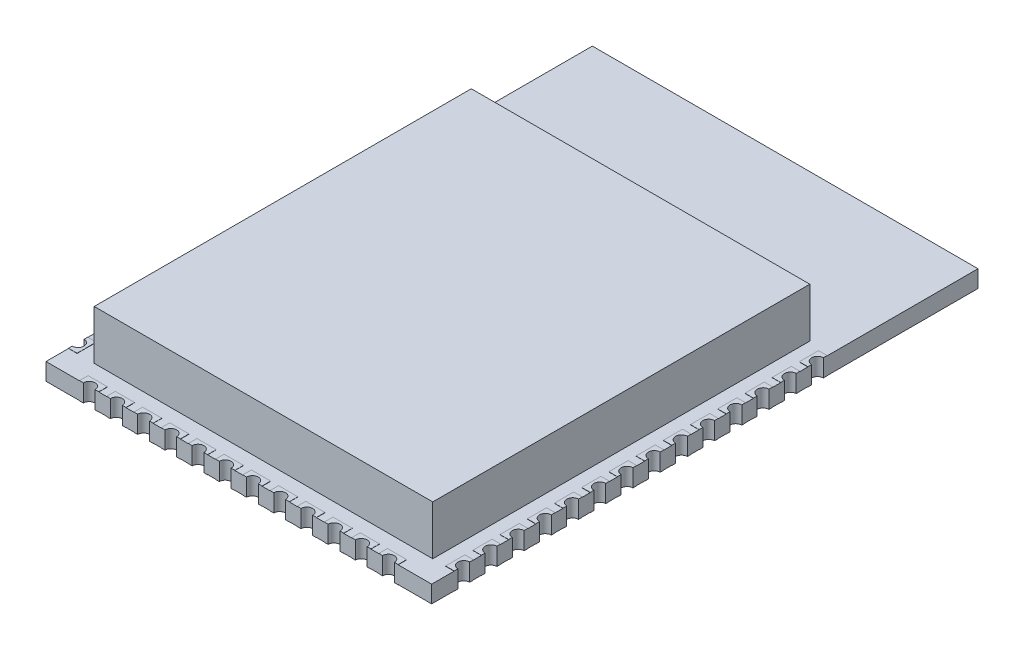
SolidWorks part; units mm, degrees
ref_plane "Front Plane" through (0, 0, 0) normal (0, 0, 1) x (1, 0, 0)
ref_plane "Top Plane" through (0, 0, 0) normal (0, 1, 0) x (1, 0, 0)
ref_plane "Right Plane" through (0, 0, 0) normal (1, 0, 0) x (0, 0, -1)
sketch "Sketch1" plane through (0, 0, 0) normal (0, 1, 0) x (1, 0, 0)
  line L5 (-9, 0) -> (9, 0)
  line L6 (-9, 0) -> (-9, -25.5)
  line L7 (-9, -25.5) -> (9, -25.5)
  line L8 (9, 0) -> (9, -25.5)
  dimension "D1" = 18
  dimension "D2" = 25.5
extrude "Boss-Extrude1" add sketch "Sketch1" along normal blind 0.8
sketch "Sketch2" plane through (0, 0.8, 0) normal (0, 1, 0) x (1, 0, 0)
  line L0 (-9, 0) -> (-9, -25.5) construction
  line L1 (-9, -23.55) -> (-8.6, -23.55)
  line L2 (-9, -23.55) -> (-9, -24.45)
  line L3 (-9, -24.45) -> (-8.6, -24.45)
  line L4 (-8.6, -23.55) -> (-8.6, -24.45)
  line L5 (-8.6, -24) -> (-6.8619, -24) construction
  line L6 (-9, -25.5) -> (9, -25.5) construction
  line L7 (-9, -23.18) -> (-8.6, -23.18)
  line L8 (-8.6, -22.28) -> (-8.6, -23.18)
  line L9 (-9, -22.28) -> (-8.6, -22.28)
  line L10 (-9, -22.28) -> (-9, -23.18)
  line L11 (-9, -21.91) -> (-8.6, -21.91)
  line L12 (-8.6, -21.01) -> (-8.6, -21.91)
  line L13 (-9, -21.01) -> (-8.6, -21.01)
  line L14 (-9, -21.01) -> (-9, -21.91)
  line L15 (-9, -20.64) -> (-8.6, -20.64)
  line L16 (-8.6, -19.74) -> (-8.6, -20.64)
  line L17 (-9, -19.74) -> (-8.6, -19.74)
  line L18 (-9, -19.74) -> (-9, -20.64)
  line L19 (-9, -19.37) -> (-8.6, -19.37)
  line L20 (-8.6, -18.47) -> (-8.6, -19.37)
  line L21 (-9, -18.47) -> (-8.6, -18.47)
  line L22 (-9, -18.47) -> (-9, -19.37)
  line L23 (-9, -18.1) -> (-8.6, -18.1)
  line L24 (-8.6, -17.2) -> (-8.6, -18.1)
  line L25 (-9, -17.2) -> (-8.6, -17.2)
  line L26 (-9, -17.2) -> (-9, -18.1)
  line L27 (-9, -16.83) -> (-8.6, -16.83)
  line L28 (-8.6, -15.93) -> (-8.6, -16.83)
  line L29 (-9, -15.93) -> (-8.6, -15.93)
  line L30 (-9, -15.93) -> (-9, -16.83)
  line L31 (-9, -15.56) -> (-8.6, -15.56)
  line L32 (-8.6, -14.66) -> (-8.6, -15.56)
  line L33 (-9, -14.66) -> (-8.6, -14.66)
  line L34 (-9, -14.66) -> (-9, -15.56)
  line L35 (-9, -14.29) -> (-8.6, -14.29)
  line L36 (-8.6, -13.39) -> (-8.6, -14.29)
  line L37 (-9, -13.39) -> (-8.6, -13.39)
  line L38 (-9, -13.39) -> (-9, -14.29)
  line L39 (-9, -13.02) -> (-8.6, -13.02)
  line L40 (-8.6, -12.12) -> (-8.6, -13.02)
  line L41 (-9, -12.12) -> (-8.6, -12.12)
  line L42 (-9, -12.12) -> (-9, -13.02)
  line L43 (-9, -11.75) -> (-8.6, -11.75)
  line L44 (-8.6, -10.85) -> (-8.6, -11.75)
  line L45 (-9, -10.85) -> (-8.6, -10.85)
  line L46 (-9, -10.85) -> (-9, -11.75)
  line L47 (-9, -10.48) -> (-8.6, -10.48)
  line L48 (-8.6, -9.58) -> (-8.6, -10.48)
  line L49 (-9, -9.58) -> (-8.6, -9.58)
  line L50 (-9, -9.58) -> (-9, -10.48)
  line L51 (-9, -9.21) -> (-8.6, -9.21)
  line L52 (-8.6, -8.31) -> (-8.6, -9.21)
  line L53 (-9, -8.31) -> (-8.6, -8.31)
  line L54 (-9, -8.31) -> (-9, -9.21)
  line L55 (-9, -7.94) -> (-8.6, -7.94)
  line L56 (-8.6, -7.04) -> (-8.6, -7.94)
  line L57 (-9, -7.04) -> (-8.6, -7.04)
  line L58 (-9, -7.04) -> (-9, -7.94)
  line L63 (-9, -6.67) -> (-8.6, -6.67) [skipped]
  line L64 (-8.6, -5.77) -> (-8.6, -6.67) [skipped]
  line L65 (-9, -5.77) -> (-8.6, -5.77) [skipped]
  line L66 (-9, -5.77) -> (-9, -6.67) [skipped]
  line L67 (0, -25.5) -> (0, -12.4849) construction
  line L68 (9, -7.04) -> (9, -7.94)
  line L69 (9, -7.04) -> (8.6, -7.04)
  line L70 (8.6, -7.04) -> (8.6, -7.94)
  line L71 (9, -7.94) -> (8.6, -7.94)
  line L72 (9, -8.31) -> (9, -9.21)
  line L73 (9, -8.31) -> (8.6, -8.31)
  line L74 (8.6, -8.31) -> (8.6, -9.21)
  line L75 (9, -9.21) -> (8.6, -9.21)
  line L76 (9, -9.58) -> (9, -10.48)
  line L77 (9, -9.58) -> (8.6, -9.58)
  line L78 (8.6, -9.58) -> (8.6, -10.48)
  line L79 (9, -10.48) -> (8.6, -10.48)
  line L80 (9, -10.85) -> (9, -11.75)
  line L81 (9, -10.85) -> (8.6, -10.85)
  line L82 (8.6, -10.85) -> (8.6, -11.75)
  line L83 (9, -11.75) -> (8.6, -11.75)
  line L84 (9, -12.12) -> (9, -13.02)
  line L85 (9, -12.12) -> (8.6, -12.12)
  line L86 (8.6, -12.12) -> (8.6, -13.02)
  line L87 (9, -13.02) -> (8.6, -13.02)
  line L88 (9, -13.39) -> (9, -14.29)
  line L89 (9, -13.39) -> (8.6, -13.39)
  line L90 (8.6, -13.39) -> (8.6, -14.29)
  line L91 (9, -14.29) -> (8.6, -14.29)
  line L92 (9, -14.66) -> (9, -15.56)
  line L93 (9, -14.66) -> (8.6, -14.66)
  line L94 (8.6, -14.66) -> (8.6, -15.56)
  line L95 (9, -15.56) -> (8.6, -15.56)
  line L96 (9, -15.93) -> (9, -16.83)
  line L97 (9, -15.93) -> (8.6, -15.93)
  line L98 (8.6, -15.93) -> (8.6, -16.83)
  line L99 (9, -16.83) -> (8.6, -16.83)
  line L100 (9, -17.2) -> (9, -18.1)
  line L101 (9, -17.2) -> (8.6, -17.2)
  line L102 (8.6, -17.2) -> (8.6, -18.1)
  line L103 (9, -18.1) -> (8.6, -18.1)
  line L104 (9, -18.47) -> (9, -19.37)
  line L105 (9, -18.47) -> (8.6, -18.47)
  line L106 (8.6, -18.47) -> (8.6, -19.37)
  line L107 (9, -19.37) -> (8.6, -19.37)
  line L108 (9, -19.74) -> (9, -20.64)
  line L109 (9, -19.74) -> (8.6, -19.74)
  line L110 (8.6, -19.74) -> (8.6, -20.64)
  line L111 (9, -20.64) -> (8.6, -20.64)
  line L112 (9, -21.01) -> (9, -21.91)
  line L113 (9, -21.01) -> (8.6, -21.01)
  line L114 (8.6, -21.01) -> (8.6, -21.91)
  line L115 (9, -21.91) -> (8.6, -21.91)
  line L116 (9, -22.28) -> (9, -23.18)
  line L117 (9, -22.28) -> (8.6, -22.28)
  line L118 (8.6, -22.28) -> (8.6, -23.18)
  line L119 (9, -23.18) -> (8.6, -23.18)
  line L120 (8.6, -23.55) -> (8.6, -24.45)
  line L121 (9, -24.45) -> (8.6, -24.45)
  line L122 (9, -23.55) -> (9, -24.45)
  line L123 (9, -23.55) -> (8.6, -23.55)
  line L124 (-6.165, -25.5) -> (-6.165, -25.1)
  line L125 (-7.435, -25.5) -> (-6.535, -25.5)
  line L126 (-7.435, -25.5) -> (-7.435, -25.1)
  line L127 (-7.435, -25.1) -> (-6.535, -25.1)
  line L128 (-6.535, -25.5) -> (-6.535, -25.1)
  line L129 (-6.165, -25.1) -> (-5.265, -25.1)
  line L130 (-5.265, -25.5) -> (-5.265, -25.1)
  line L131 (-6.165, -25.5) -> (-5.265, -25.5)
  line L132 (-4.895, -25.5) -> (-4.895, -25.1)
  line L133 (-4.895, -25.1) -> (-3.995, -25.1)
  line L134 (-3.995, -25.5) -> (-3.995, -25.1)
  line L135 (-4.895, -25.5) -> (-3.995, -25.5)
  line L136 (-3.625, -25.5) -> (-3.625, -25.1)
  line L137 (-3.625, -25.1) -> (-2.725, -25.1)
  line L138 (-2.725, -25.5) -> (-2.725, -25.1)
  line L139 (-3.625, -25.5) -> (-2.725, -25.5)
  line L140 (-2.355, -25.5) -> (-2.355, -25.1)
  line L141 (-2.355, -25.1) -> (-1.455, -25.1)
  line L142 (-1.455, -25.5) -> (-1.455, -25.1)
  line L143 (-2.355, -25.5) -> (-1.455, -25.5)
  line L144 (-1.085, -25.5) -> (-1.085, -25.1)
  line L145 (-1.085, -25.1) -> (-0.185, -25.1)
  line L146 (-0.185, -25.5) -> (-0.185, -25.1)
  line L147 (-1.085, -25.5) -> (-0.185, -25.5)
  line L148 (0.185, -25.5) -> (0.185, -25.1)
  line L149 (0.185, -25.1) -> (1.085, -25.1)
  line L150 (1.085, -25.5) -> (1.085, -25.1)
  line L151 (0.185, -25.5) -> (1.085, -25.5)
  line L152 (1.455, -25.5) -> (1.455, -25.1)
  line L153 (1.455, -25.1) -> (2.355, -25.1)
  line L154 (2.355, -25.5) -> (2.355, -25.1)
  line L155 (1.455, -25.5) -> (2.355, -25.5)
  line L156 (2.725, -25.5) -> (2.725, -25.1)
  line L157 (2.725, -25.1) -> (3.625, -25.1)
  line L158 (3.625, -25.5) -> (3.625, -25.1)
  line L159 (2.725, -25.5) -> (3.625, -25.5)
  line L160 (3.995, -25.5) -> (3.995, -25.1)
  line L161 (3.995, -25.1) -> (4.895, -25.1)
  line L162 (4.895, -25.5) -> (4.895, -25.1)
  line L163 (3.995, -25.5) -> (4.895, -25.5)
  line L164 (5.265, -25.5) -> (5.265, -25.1)
  line L165 (5.265, -25.1) -> (6.165, -25.1)
  line L166 (6.165, -25.5) -> (6.165, -25.1)
  line L167 (5.265, -25.5) -> (6.165, -25.5)
  line L168 (6.535, -25.5) -> (6.535, -25.1)
  line L169 (6.535, -25.1) -> (7.435, -25.1)
  line L170 (7.435, -25.5) -> (7.435, -25.1)
  line L171 (6.535, -25.5) -> (7.435, -25.5)
  point P10 (-9, -7.49)
  point P11 (-9, -8.76)
  point P131 (9, -8.76)
  point P132 (9, -7.49)
  point P137 (-6.985, -25.5)
  point P138 (6.985, -25.5)
  point P183 (-5.715, -25.5)
  dimension "D1" = 0.4
  dimension "D2" = 1.5
  dimension "D3" = 0.9
  dimension "D5" = 16.51
  dimension "D6" = 12
  dimension "D7" = 1.27
  dimension "D8" = 13.97
  dimension "D4" = 15
extrude "Boss-Extrude2" add sketch "Sketch2" along normal blind 0.01
sketch "Sketch3" plane through (0, 0, 0) normal (0, -1, 0) x (1, 0, 0)
  line L0 (-9, 9.58) -> (-9, 10.48) construction
  line L1 (-9, 10.48) -> (-8.6, 10.48) construction
  line L2 (-8.6, 10.48) -> (-8.6, 9.58) construction
  line L3 (-8.6, 9.58) -> (-9, 9.58) construction
  line L4 (-9, 8.31) -> (-9, 9.21) construction
  line L5 (-9, 9.21) -> (-8.6, 9.21) construction
  line L6 (-8.6, 9.21) -> (-8.6, 8.31) construction
  line L7 (-8.6, 8.31) -> (-9, 8.31) construction
  line L8 (-9, 7.04) -> (-9, 7.94) construction
  line L9 (-9, 7.94) -> (-8.6, 7.94) construction
  line L10 (-8.6, 7.94) -> (-8.6, 7.04) construction
  line L11 (-8.6, 7.04) -> (-9, 7.04) construction
  line L12 (-9, 9.58) -> (-9, 10.48)
  line L13 (-9, 10.48) -> (-8.6, 10.48)
  line L14 (-8.6, 10.48) -> (-8.6, 9.58)
  line L15 (-8.6, 9.58) -> (-9, 9.58)
  line L16 (-9, 8.31) -> (-9, 9.21)
  line L17 (-9, 9.21) -> (-8.6, 9.21)
  line L18 (-8.6, 9.21) -> (-8.6, 8.31)
  line L19 (-8.6, 8.31) -> (-9, 8.31)
  line L20 (-9, 7.04) -> (-9, 7.94)
  line L21 (-9, 7.94) -> (-8.6, 7.94)
  line L22 (-8.6, 7.94) -> (-8.6, 7.04)
  line L23 (-8.6, 7.04) -> (-9, 7.04)
  line L24 (-9, 17.2) -> (-9, 18.1) construction
  line L25 (-9, 18.1) -> (-8.6, 18.1) construction
  line L26 (-8.6, 18.1) -> (-8.6, 17.2) construction
  line L27 (-8.6, 17.2) -> (-9, 17.2) construction
  line L28 (-9, 15.93) -> (-9, 16.83) construction
  line L29 (-9, 16.83) -> (-8.6, 16.83) construction
  line L30 (-8.6, 16.83) -> (-8.6, 15.93) construction
  line L31 (-8.6, 15.93) -> (-9, 15.93) construction
  line L32 (-9, 14.66) -> (-9, 15.56) construction
  line L33 (-9, 15.56) -> (-8.6, 15.56) construction
  line L34 (-8.6, 15.56) -> (-8.6, 14.66) construction
  line L35 (-8.6, 14.66) -> (-9, 14.66) construction
  line L36 (-9, 13.39) -> (-9, 14.29) construction
  line L37 (-9, 14.29) -> (-8.6, 14.29) construction
  line L38 (-8.6, 14.29) -> (-8.6, 13.39) construction
  line L39 (-8.6, 13.39) -> (-9, 13.39) construction
  line L40 (-9, 12.12) -> (-9, 13.02) construction
  line L41 (-9, 13.02) -> (-8.6, 13.02) construction
  line L42 (-8.6, 13.02) -> (-8.6, 12.12) construction
  line L43 (-8.6, 12.12) -> (-9, 12.12) construction
  line L44 (-9, 10.85) -> (-9, 11.75) construction
  line L45 (-9, 11.75) -> (-8.6, 11.75) construction
  line L46 (-8.6, 11.75) -> (-8.6, 10.85) construction
  line L47 (-8.6, 10.85) -> (-9, 10.85) construction
  line L48 (-9, 17.2) -> (-9, 18.1)
  line L49 (-9, 18.1) -> (-8.6, 18.1)
  line L50 (-8.6, 18.1) -> (-8.6, 17.2)
  line L51 (-8.6, 17.2) -> (-9, 17.2)
  line L52 (-9, 15.93) -> (-9, 16.83)
  line L53 (-9, 16.83) -> (-8.6, 16.83)
  line L54 (-8.6, 16.83) -> (-8.6, 15.93)
  line L55 (-8.6, 15.93) -> (-9, 15.93)
  line L56 (-9, 14.66) -> (-9, 15.56)
  line L57 (-9, 15.56) -> (-8.6, 15.56)
  line L58 (-8.6, 15.56) -> (-8.6, 14.66)
  line L59 (-8.6, 14.66) -> (-9, 14.66)
  line L60 (-9, 13.39) -> (-9, 14.29)
  line L61 (-9, 14.29) -> (-8.6, 14.29)
  line L62 (-8.6, 14.29) -> (-8.6, 13.39)
  line L63 (-8.6, 13.39) -> (-9, 13.39)
  line L64 (-9, 12.12) -> (-9, 13.02)
  line L65 (-9, 13.02) -> (-8.6, 13.02)
  line L66 (-8.6, 13.02) -> (-8.6, 12.12)
  line L67 (-8.6, 12.12) -> (-9, 12.12)
  line L68 (-9, 10.85) -> (-9, 11.75)
  line L69 (-9, 11.75) -> (-8.6, 11.75)
  line L70 (-8.6, 11.75) -> (-8.6, 10.85)
  line L71 (-8.6, 10.85) -> (-9, 10.85)
  line L72 (-9, 23.55) -> (-9, 24.45) construction
  line L73 (-9, 24.45) -> (-8.6, 24.45) construction
  line L74 (-8.6, 24.45) -> (-8.6, 23.55) construction
  line L75 (-8.6, 23.55) -> (-9, 23.55) construction
  line L76 (-9, 22.28) -> (-9, 23.18) construction
  line L77 (-9, 23.18) -> (-8.6, 23.18) construction
  line L78 (-8.6, 23.18) -> (-8.6, 22.28) construction
  line L79 (-8.6, 22.28) -> (-9, 22.28) construction
  line L80 (-9, 21.01) -> (-9, 21.91) construction
  line L81 (-9, 21.91) -> (-8.6, 21.91) construction
  line L82 (-8.6, 21.91) -> (-8.6, 21.01) construction
  line L83 (-8.6, 21.01) -> (-9, 21.01) construction
  line L84 (-9, 19.74) -> (-9, 20.64) construction
  line L85 (-9, 20.64) -> (-8.6, 20.64) construction
  line L86 (-8.6, 20.64) -> (-8.6, 19.74) construction
  line L87 (-8.6, 19.74) -> (-9, 19.74) construction
  line L88 (-9, 18.47) -> (-9, 19.37) construction
  line L89 (-9, 19.37) -> (-8.6, 19.37) construction
  line L90 (-8.6, 19.37) -> (-8.6, 18.47) construction
  line L91 (-8.6, 18.47) -> (-9, 18.47) construction
  line L92 (-9, 23.55) -> (-9, 24.45)
  line L93 (-9, 24.45) -> (-8.6, 24.45)
  line L94 (-8.6, 24.45) -> (-8.6, 23.55)
  line L95 (-8.6, 23.55) -> (-9, 23.55)
  line L96 (-9, 22.28) -> (-9, 23.18)
  line L97 (-9, 23.18) -> (-8.6, 23.18)
  line L98 (-8.6, 23.18) -> (-8.6, 22.28)
  line L99 (-8.6, 22.28) -> (-9, 22.28)
  line L100 (-9, 21.01) -> (-9, 21.91)
  line L101 (-9, 21.91) -> (-8.6, 21.91)
  line L102 (-8.6, 21.91) -> (-8.6, 21.01)
  line L103 (-8.6, 21.01) -> (-9, 21.01)
  line L104 (-9, 19.74) -> (-9, 20.64)
  line L105 (-9, 20.64) -> (-8.6, 20.64)
  line L106 (-8.6, 20.64) -> (-8.6, 19.74)
  line L107 (-8.6, 19.74) -> (-9, 19.74)
  line L108 (-9, 18.47) -> (-9, 19.37)
  line L109 (-9, 19.37) -> (-8.6, 19.37)
  line L110 (-8.6, 19.37) -> (-8.6, 18.47)
  line L111 (-8.6, 18.47) -> (-9, 18.47)
  line L112 (6.535, 25.5) -> (7.435, 25.5) construction
  line L113 (7.435, 25.5) -> (7.435, 25.1) construction
  line L114 (7.435, 25.1) -> (6.535, 25.1) construction
  line L115 (6.535, 25.1) -> (6.535, 25.5) construction
  line L116 (5.265, 25.5) -> (6.165, 25.5) construction
  line L117 (6.165, 25.5) -> (6.165, 25.1) construction
  line L118 (6.165, 25.1) -> (5.265, 25.1) construction
  line L119 (5.265, 25.1) -> (5.265, 25.5) construction
  line L120 (3.995, 25.5) -> (4.895, 25.5) construction
  line L121 (4.895, 25.5) -> (4.895, 25.1) construction
  line L122 (4.895, 25.1) -> (3.995, 25.1) construction
  line L123 (3.995, 25.1) -> (3.995, 25.5) construction
  line L124 (2.725, 25.5) -> (3.625, 25.5) construction
  line L125 (3.625, 25.5) -> (3.625, 25.1) construction
  line L126 (3.625, 25.1) -> (2.725, 25.1) construction
  line L127 (2.725, 25.1) -> (2.725, 25.5) construction
  line L128 (1.455, 25.5) -> (2.355, 25.5) construction
  line L129 (2.355, 25.5) -> (2.355, 25.1) construction
  line L130 (2.355, 25.1) -> (1.455, 25.1) construction
  line L131 (1.455, 25.1) -> (1.455, 25.5) construction
  line L132 (0.185, 25.5) -> (1.085, 25.5) construction
  line L133 (1.085, 25.5) -> (1.085, 25.1) construction
  line L134 (1.085, 25.1) -> (0.185, 25.1) construction
  line L135 (0.185, 25.1) -> (0.185, 25.5) construction
  line L136 (-1.085, 25.5) -> (-0.185, 25.5) construction
  line L137 (-0.185, 25.5) -> (-0.185, 25.1) construction
  line L138 (-0.185, 25.1) -> (-1.085, 25.1) construction
  line L139 (-1.085, 25.1) -> (-1.085, 25.5) construction
  line L140 (-2.355, 25.5) -> (-1.455, 25.5) construction
  line L141 (-1.455, 25.5) -> (-1.455, 25.1) construction
  line L142 (-1.455, 25.1) -> (-2.355, 25.1) construction
  line L143 (-2.355, 25.1) -> (-2.355, 25.5) construction
  line L144 (-3.625, 25.5) -> (-2.725, 25.5) construction
  line L145 (-2.725, 25.5) -> (-2.725, 25.1) construction
  line L146 (-2.725, 25.1) -> (-3.625, 25.1) construction
  line L147 (-3.625, 25.1) -> (-3.625, 25.5) construction
  line L148 (-4.895, 25.5) -> (-3.995, 25.5) construction
  line L149 (-3.995, 25.5) -> (-3.995, 25.1) construction
  line L150 (-3.995, 25.1) -> (-4.895, 25.1) construction
  line L151 (-4.895, 25.1) -> (-4.895, 25.5) construction
  line L152 (-6.165, 25.5) -> (-5.265, 25.5) construction
  line L153 (-5.265, 25.5) -> (-5.265, 25.1) construction
  line L154 (-5.265, 25.1) -> (-6.165, 25.1) construction
  line L155 (-6.165, 25.1) -> (-6.165, 25.5) construction
  line L156 (-7.435, 25.1) -> (-7.435, 25.5) construction
  line L157 (-7.435, 25.5) -> (-6.535, 25.5) construction
  line L158 (-6.535, 25.5) -> (-6.535, 25.1) construction
  line L159 (-6.535, 25.1) -> (-7.435, 25.1) construction
  line L160 (6.535, 25.5) -> (7.435, 25.5)
  line L161 (7.435, 25.5) -> (7.435, 25.1)
  line L162 (7.435, 25.1) -> (6.535, 25.1)
  line L163 (6.535, 25.1) -> (6.535, 25.5)
  line L164 (5.265, 25.5) -> (6.165, 25.5)
  line L165 (6.165, 25.5) -> (6.165, 25.1)
  line L166 (6.165, 25.1) -> (5.265, 25.1)
  line L167 (5.265, 25.1) -> (5.265, 25.5)
  line L168 (3.995, 25.5) -> (4.895, 25.5)
  line L169 (4.895, 25.5) -> (4.895, 25.1)
  line L170 (4.895, 25.1) -> (3.995, 25.1)
  line L171 (3.995, 25.1) -> (3.995, 25.5)
  line L172 (2.725, 25.5) -> (3.625, 25.5)
  line L173 (3.625, 25.5) -> (3.625, 25.1)
  line L174 (3.625, 25.1) -> (2.725, 25.1)
  line L175 (2.725, 25.1) -> (2.725, 25.5)
  line L176 (1.455, 25.5) -> (2.355, 25.5)
  line L177 (2.355, 25.5) -> (2.355, 25.1)
  line L178 (2.355, 25.1) -> (1.455, 25.1)
  line L179 (1.455, 25.1) -> (1.455, 25.5)
  line L180 (0.185, 25.5) -> (1.085, 25.5)
  line L181 (1.085, 25.5) -> (1.085, 25.1)
  line L182 (1.085, 25.1) -> (0.185, 25.1)
  line L183 (0.185, 25.1) -> (0.185, 25.5)
  line L184 (-1.085, 25.5) -> (-0.185, 25.5)
  line L185 (-0.185, 25.5) -> (-0.185, 25.1)
  line L186 (-0.185, 25.1) -> (-1.085, 25.1)
  line L187 (-1.085, 25.1) -> (-1.085, 25.5)
  line L188 (-2.355, 25.5) -> (-1.455, 25.5)
  line L189 (-1.455, 25.5) -> (-1.455, 25.1)
  line L190 (-1.455, 25.1) -> (-2.355, 25.1)
  line L191 (-2.355, 25.1) -> (-2.355, 25.5)
  line L192 (-3.625, 25.5) -> (-2.725, 25.5)
  line L193 (-2.725, 25.5) -> (-2.725, 25.1)
  line L194 (-2.725, 25.1) -> (-3.625, 25.1)
  line L195 (-3.625, 25.1) -> (-3.625, 25.5)
  line L196 (-4.895, 25.5) -> (-3.995, 25.5)
  line L197 (-3.995, 25.5) -> (-3.995, 25.1)
  line L198 (-3.995, 25.1) -> (-4.895, 25.1)
  line L199 (-4.895, 25.1) -> (-4.895, 25.5)
  line L200 (-6.165, 25.5) -> (-5.265, 25.5)
  line L201 (-5.265, 25.5) -> (-5.265, 25.1)
  line L202 (-5.265, 25.1) -> (-6.165, 25.1)
  line L203 (-6.165, 25.1) -> (-6.165, 25.5)
  line L204 (-7.435, 25.1) -> (-7.435, 25.5)
  line L205 (-7.435, 25.5) -> (-6.535, 25.5)
  line L206 (-6.535, 25.5) -> (-6.535, 25.1)
  line L207 (-6.535, 25.1) -> (-7.435, 25.1)
  line L208 (9, 17.2) -> (8.6, 17.2) construction
  line L209 (8.6, 17.2) -> (8.6, 18.1) construction
  line L210 (8.6, 18.1) -> (9, 18.1) construction
  line L211 (9, 18.1) -> (9, 17.2) construction
  line L212 (9, 18.47) -> (8.6, 18.47) construction
  line L213 (8.6, 18.47) -> (8.6, 19.37) construction
  line L214 (8.6, 19.37) -> (9, 19.37) construction
  line L215 (9, 19.37) -> (9, 18.47) construction
  line L216 (9, 19.74) -> (8.6, 19.74) construction
  line L217 (8.6, 19.74) -> (8.6, 20.64) construction
  line L218 (8.6, 20.64) -> (9, 20.64) construction
  line L219 (9, 20.64) -> (9, 19.74) construction
  line L220 (9, 21.01) -> (8.6, 21.01) construction
  line L221 (8.6, 21.01) -> (8.6, 21.91) construction
  line L222 (8.6, 21.91) -> (9, 21.91) construction
  line L223 (9, 21.91) -> (9, 21.01) construction
  line L224 (9, 22.28) -> (8.6, 22.28) construction
  line L225 (8.6, 22.28) -> (8.6, 23.18) construction
  line L226 (8.6, 23.18) -> (9, 23.18) construction
  line L227 (9, 23.18) -> (9, 22.28) construction
  line L228 (9, 23.55) -> (8.6, 23.55) construction
  line L229 (8.6, 23.55) -> (8.6, 24.45) construction
  line L230 (8.6, 24.45) -> (9, 24.45) construction
  line L231 (9, 24.45) -> (9, 23.55) construction
  line L232 (9, 17.2) -> (8.6, 17.2)
  line L233 (8.6, 17.2) -> (8.6, 18.1)
  line L234 (8.6, 18.1) -> (9, 18.1)
  line L235 (9, 18.1) -> (9, 17.2)
  line L236 (9, 18.47) -> (8.6, 18.47)
  line L237 (8.6, 18.47) -> (8.6, 19.37)
  line L238 (8.6, 19.37) -> (9, 19.37)
  line L239 (9, 19.37) -> (9, 18.47)
  line L240 (9, 19.74) -> (8.6, 19.74)
  line L241 (8.6, 19.74) -> (8.6, 20.64)
  line L242 (8.6, 20.64) -> (9, 20.64)
  line L243 (9, 20.64) -> (9, 19.74)
  line L244 (9, 21.01) -> (8.6, 21.01)
  line L245 (8.6, 21.01) -> (8.6, 21.91)
  line L246 (8.6, 21.91) -> (9, 21.91)
  line L247 (9, 21.91) -> (9, 21.01)
  line L248 (9, 22.28) -> (8.6, 22.28)
  line L249 (8.6, 22.28) -> (8.6, 23.18)
  line L250 (8.6, 23.18) -> (9, 23.18)
  line L251 (9, 23.18) -> (9, 22.28)
  line L252 (9, 23.55) -> (8.6, 23.55)
  line L253 (8.6, 23.55) -> (8.6, 24.45)
  line L254 (8.6, 24.45) -> (9, 24.45)
  line L255 (9, 24.45) -> (9, 23.55)
  line L256 (9, 7.04) -> (8.6, 7.04) construction
  line L257 (8.6, 7.04) -> (8.6, 7.94) construction
  line L258 (8.6, 7.94) -> (9, 7.94) construction
  line L259 (9, 7.94) -> (9, 7.04) construction
  line L260 (9, 8.31) -> (8.6, 8.31) construction
  line L261 (8.6, 8.31) -> (8.6, 9.21) construction
  line L262 (8.6, 9.21) -> (9, 9.21) construction
  line L263 (9, 9.21) -> (9, 8.31) construction
  line L264 (9, 9.58) -> (8.6, 9.58) construction
  line L265 (8.6, 9.58) -> (8.6, 10.48) construction
  line L266 (8.6, 10.48) -> (9, 10.48) construction
  line L267 (9, 10.48) -> (9, 9.58) construction
  line L268 (9, 10.85) -> (8.6, 10.85) construction
  line L269 (8.6, 10.85) -> (8.6, 11.75) construction
  line L270 (8.6, 11.75) -> (9, 11.75) construction
  line L271 (9, 11.75) -> (9, 10.85) construction
  line L272 (9, 12.12) -> (8.6, 12.12) construction
  line L273 (8.6, 12.12) -> (8.6, 13.02) construction
  line L274 (8.6, 13.02) -> (9, 13.02) construction
  line L275 (9, 13.02) -> (9, 12.12) construction
  line L276 (9, 13.39) -> (8.6, 13.39) construction
  line L277 (8.6, 13.39) -> (8.6, 14.29) construction
  line L278 (8.6, 14.29) -> (9, 14.29) construction
  line L279 (9, 14.29) -> (9, 13.39) construction
  line L280 (9, 14.66) -> (8.6, 14.66) construction
  line L281 (8.6, 14.66) -> (8.6, 15.56) construction
  line L282 (8.6, 15.56) -> (9, 15.56) construction
  line L283 (9, 15.56) -> (9, 14.66) construction
  line L284 (9, 15.93) -> (8.6, 15.93) construction
  line L285 (8.6, 15.93) -> (8.6, 16.83) construction
  line L286 (8.6, 16.83) -> (9, 16.83) construction
  line L287 (9, 16.83) -> (9, 15.93) construction
  line L288 (9, 7.04) -> (8.6, 7.04)
  line L289 (8.6, 7.04) -> (8.6, 7.94)
  line L290 (8.6, 7.94) -> (9, 7.94)
  line L291 (9, 7.94) -> (9, 7.04)
  line L292 (9, 8.31) -> (8.6, 8.31)
  line L293 (8.6, 8.31) -> (8.6, 9.21)
  line L294 (8.6, 9.21) -> (9, 9.21)
  line L295 (9, 9.21) -> (9, 8.31)
  line L296 (9, 9.58) -> (8.6, 9.58)
  line L297 (8.6, 9.58) -> (8.6, 10.48)
  line L298 (8.6, 10.48) -> (9, 10.48)
  line L299 (9, 10.48) -> (9, 9.58)
  line L300 (9, 10.85) -> (8.6, 10.85)
  line L301 (8.6, 10.85) -> (8.6, 11.75)
  line L302 (8.6, 11.75) -> (9, 11.75)
  line L303 (9, 11.75) -> (9, 10.85)
  line L304 (9, 12.12) -> (8.6, 12.12)
  line L305 (8.6, 12.12) -> (8.6, 13.02)
  line L306 (8.6, 13.02) -> (9, 13.02)
  line L307 (9, 13.02) -> (9, 12.12)
  line L308 (9, 13.39) -> (8.6, 13.39)
  line L309 (8.6, 13.39) -> (8.6, 14.29)
  line L310 (8.6, 14.29) -> (9, 14.29)
  line L311 (9, 14.29) -> (9, 13.39)
  line L312 (9, 14.66) -> (8.6, 14.66)
  line L313 (8.6, 14.66) -> (8.6, 15.56)
  line L314 (8.6, 15.56) -> (9, 15.56)
  line L315 (9, 15.56) -> (9, 14.66)
  line L316 (9, 15.93) -> (8.6, 15.93)
  line L317 (8.6, 15.93) -> (8.6, 16.83)
  line L318 (8.6, 16.83) -> (9, 16.83)
  line L319 (9, 16.83) -> (9, 15.93)
extrude "Boss-Extrude3" add sketch "Sketch3" along normal blind 0.01
sketch "Sketch4" plane through (0, 0.8, 0) normal (0, 1, 0) x (1, 0, 0)
  line L0 (0, 0) -> (0, -9.3125) construction
  line L1 (-7.8, -6.85) -> (8, -6.85)
  line L2 (-7.8, -6.85) -> (-7.8, -24.45)
  line L3 (-7.8, -24.45) -> (8, -24.45)
  line L4 (8, -6.85) -> (8, -24.45)
  line L5 (7.435, -25.5) -> (9, -25.5) construction
  line L8 (9, -25.5) -> (9, -24.45) construction
  dimension "D1" = 1.05
  dimension "D2" = 17.6
  dimension "D3" = 15.8
  dimension "D4" = 1
extrude "Boss-Extrude4" add sketch "Sketch4" along normal blind 2.3
sketch "Sketch5" plane through (0, 0.81, 0) normal (0, 1, 0) x (1, 0, 0)
  line L0 (-9, -7.04) -> (-9, -7.94) construction
  line L1 (0, 0) -> (0, -8.76) construction
  line L2 (-7.435, -25.5) -> (-6.535, -25.5) construction
  circle A0 centre (-9, -7.49) radius 0.275
  circle A1 centre (-9, -8.76) radius 0.275
  circle A2 centre (-9, -10.03) radius 0.275
  circle A3 centre (-9, -11.3) radius 0.275
  circle A4 centre (-9, -12.57) radius 0.275
  circle A5 centre (-9, -13.84) radius 0.275
  circle A6 centre (-9, -15.11) radius 0.275
  circle A7 centre (-9, -16.38) radius 0.275
  circle A8 centre (-9, -17.65) radius 0.275
  circle A9 centre (-9, -18.92) radius 0.275
  circle A10 centre (-9, -20.19) radius 0.275
  circle A11 centre (-9, -21.46) radius 0.275
  circle A12 centre (-9, -22.73) radius 0.275
  circle A13 centre (-9, -24) radius 0.275
  circle A14 centre (9, -24) radius 0.275
  circle A15 centre (9, -22.73) radius 0.275
  circle A16 centre (9, -21.46) radius 0.275
  circle A17 centre (9, -20.19) radius 0.275
  circle A18 centre (9, -18.92) radius 0.275
  circle A19 centre (9, -17.65) radius 0.275
  circle A20 centre (9, -16.38) radius 0.275
  circle A21 centre (9, -15.11) radius 0.275
  circle A22 centre (9, -13.84) radius 0.275
  circle A23 centre (9, -12.57) radius 0.275
  circle A24 centre (9, -11.3) radius 0.275
  circle A25 centre (9, -10.03) radius 0.275
  circle A26 centre (9, -8.76) radius 0.275
  circle A27 centre (9, -7.49) radius 0.275
  circle A28 centre (-6.985, -25.5) radius 0.275
  circle A29 centre (-5.715, -25.5) radius 0.275
  circle A30 centre (-4.445, -25.5) radius 0.275
  circle A31 centre (-3.175, -25.5) radius 0.275
  circle A32 centre (-1.905, -25.5) radius 0.275
  circle A33 centre (-0.635, -25.5) radius 0.275
  circle A34 centre (0.635, -25.5) radius 0.275
  circle A35 centre (1.905, -25.5) radius 0.275
  circle A36 centre (3.175, -25.5) radius 0.275
  circle A37 centre (4.445, -25.5) radius 0.275
  circle A38 centre (5.715, -25.5) radius 0.275
  circle A39 centre (6.985, -25.5) radius 0.275
  dimension "D1" = 0.55
  dimension "D3" = 16.51
  dimension "D4" = 12
  dimension "D5" = 13.97
  dimension "D2" = 14
extrude "Cut-Extrude1" cut sketch "Sketch5" against normal through all
sketch "Sketch6" plane through (0, 0, 0) normal (0, -1, 0) x (-1, 0, 0)
  line L0 (1.36, -12.84) -> (1.36, -6.91) construction
  line L1 (1.36, -12.84) -> (10.9534, -12.84) construction
  line L2 (9, -25.5) -> (7.435, -25.5) construction
  line L3 (-9, -7.04) -> (-9, 0) construction
  line L4 (0.86, -11.84) -> (0.86, -10.84)
  line L5 (1.86, -13.34) -> (0.86, -13.34)
  line L6 (1.86, -13.34) -> (1.86, -12.34)
  line L7 (1.86, -12.34) -> (0.86, -12.34)
  line L8 (0.86, -13.34) -> (0.86, -12.34)
  line L9 (1.86, -13.34) -> (0.86, -12.34) construction
  line L10 (1.86, -12.34) -> (0.86, -13.34) construction
  line L11 (1.86, -10.84) -> (0.86, -10.84)
  line L12 (1.86, -11.84) -> (1.86, -10.84)
  line L13 (1.86, -11.84) -> (0.86, -11.84)
  line L14 (0.86, -13.84) -> (0.86, -14.84)
  line L15 (1.86, -14.84) -> (0.86, -14.84)
  line L16 (1.86, -13.84) -> (1.86, -14.84)
  line L17 (1.86, -13.84) -> (0.86, -13.84)
  line L18 (2.36, -13.84) -> (2.36, -14.84)
  line L19 (3.36, -14.84) -> (2.36, -14.84)
  line L20 (3.36, -13.84) -> (3.36, -14.84)
  line L21 (3.36, -13.84) -> (2.36, -13.84)
  line L22 (3.36, -13.34) -> (2.36, -13.34)
  line L23 (3.36, -13.34) -> (3.36, -12.34)
  line L24 (3.36, -12.34) -> (2.36, -12.34)
  line L25 (2.36, -13.34) -> (2.36, -12.34)
  line L26 (3.36, -11.84) -> (2.36, -11.84)
  line L27 (3.36, -11.84) -> (3.36, -10.84)
  line L28 (3.36, -10.84) -> (2.36, -10.84)
  line L29 (2.36, -11.84) -> (2.36, -10.84)
  line L30 (0.36, -11.84) -> (0.36, -10.84)
  line L31 (-0.64, -10.84) -> (0.36, -10.84)
  line L32 (-0.64, -11.84) -> (-0.64, -10.84)
  line L33 (-0.64, -11.84) -> (0.36, -11.84)
  line L34 (0.36, -13.34) -> (0.36, -12.34)
  line L35 (-0.64, -12.34) -> (0.36, -12.34)
  line L36 (-0.64, -13.34) -> (-0.64, -12.34)
  line L37 (-0.64, -13.34) -> (0.36, -13.34)
  line L38 (-0.64, -13.84) -> (0.36, -13.84)
  line L39 (-0.64, -13.84) -> (-0.64, -14.84)
  line L40 (-0.64, -14.84) -> (0.36, -14.84)
  line L41 (0.36, -13.84) -> (0.36, -14.84)
  dimension "D1" = 12.66
  dimension "D2" = 10.36
  dimension "D3" = 1
  dimension "D4" = 2
  dimension "D5" = 0.5
  dimension "D7" = 0.5
  dimension "D6" = 2
extrude "Boss-Extrude5" add sketch "Sketch6" along normal blind 0.001
